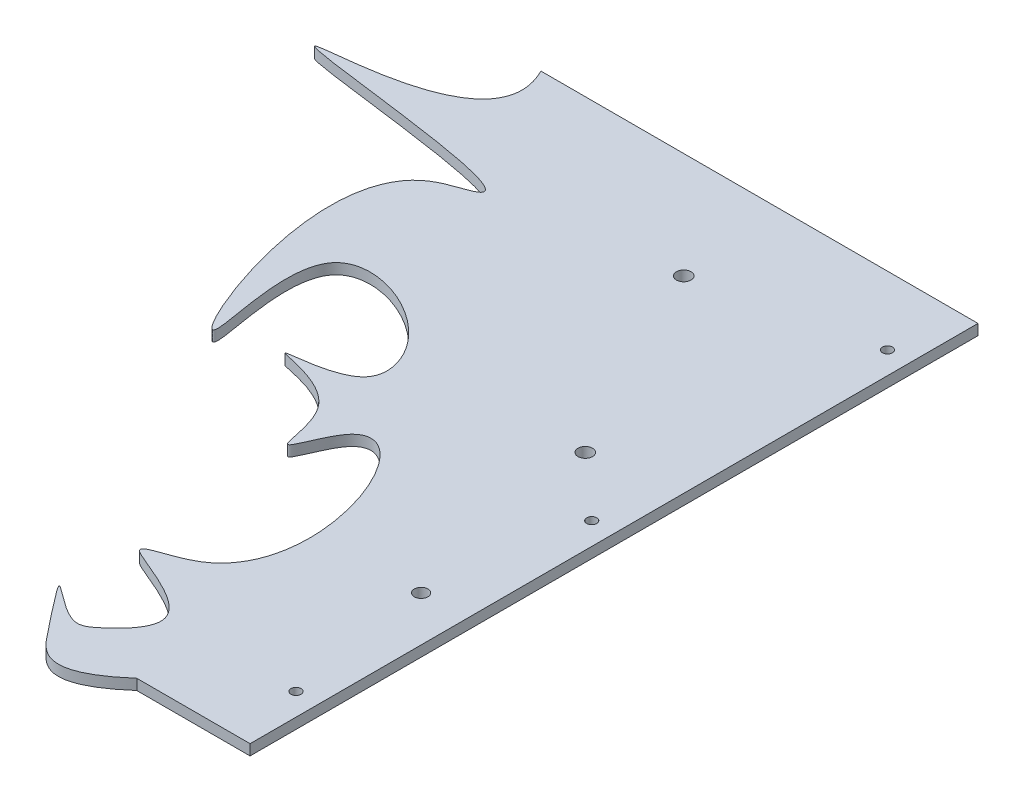
SolidWorks part; units mm, degrees
ref_plane "Front Plane" through (0, 0, 0) normal (0, 0, 1) x (1, 0, 0)
ref_plane "Top Plane" through (0, 0, 0) normal (0, 1, 0) x (1, 0, 0)
ref_plane "Right Plane" through (0, 0, 0) normal (1, 0, 0) x (0, 0, -1)
sketch "Sketch1" plane through (0, 0, 0) normal (0, 1, 0) x (1, 0, 0)
  line L0 (23.9141, 88.9) -> (-90.3859, 203.2)
  line L1 (0, 0) -> (50.8, 0)
  line L2 (0, 0) -> (0, 203.2)
  line L3 (0, 203.2) -> (50.8, 203.2)
  line L4 (50.8, 0) -> (50.8, 203.2)
  line L6 (0, 101.6) -> (0, 203.2)
  line L9 (-90.3859, 203.2) -> (0, 203.2)
  circle A0 centre (19.05, 60.325) radius 1.905
  circle A1 centre (25.4, 19.05) radius 1.397
  circle A3 centre (25.4, 101.6) radius 1.397
  circle A4 centre (25.4, 184.15) radius 1.397
  circle A5 centre (-20.9229, 173.6125) radius 2.032
  circle A6 centre (8.0019, 117.1958) radius 2.032
  point P20 (8.0019, 117.1958)
  point P21 (-20.9229, 173.6125)
  dimension "D3" = 3.81
  dimension "D9" = 2.794
  dimension "D14" = 4.064
  dimension "D15" = 4.064
  dimension "D1" = 203.2
  dimension "D2" = 50.8
  dimension "D4" = 26.8859
  dimension "D5" = 19.05
  dimension "D6" = 25.4
  dimension "D7" = 45
  dimension "D8" = 88.9
  dimension "D11" = 19.05
  dimension "D12" = 60.325
  dimension "D13" = 31.75
  dimension "D10" = 3
extrude "Boss-Extrude1" add sketch "Sketch1" along normal blind 2.9718
fillet "Fillet2" [suppressed] radius 17.78
sketch "Sketch2" plane through (0, 2.9718, 0) normal (0, 1, 0) x (1, 0, 0)
  spline S0 degree 3 poles (0, 0) (-14.4646, -12.6957) (-45.3662, 26.0149) (-25.2914, 1.7903) (-15.7444, 7.8074) (-4.3611, 20.2164) (-20.9257, 26.8985) (-34.3907, 32.6052) (7.6752, 37.8722) (-23.3746, 114.6978) (-36.7042, 69.8936) (-36.1315, 97.5495) (-70.6417, 99.5006) (-37.8553, 100.4968) (-40.7565, 124.8386) (-85.4308, 143.1876) (-60.951, 57.652) (-103.8239, 156.5637) (-47.6309, 169.6474) (-186.5705, 180.2361) (-78.0053, 178.492) (-90.3859, 203.2) knots 0 0 0 0 0.007218 0.04533 0.054764 0.083217 0.130285 0.137597 0.165213 0.280552 0.307038 0.338457 0.381582 0.421093 0.443122 0.520121 0.590944 0.735519 0.757642 0.887963 1 1 1 1
  point P2 (0, 0)
  point P4 (0, 0)
  point P6 (0, 0)
  point P8 (-90.3859, 203.2)
extrude "Boss-Extrude2" add sketch "Sketch2" against normal blind 2.9718
sketch "Sketch3" plane through (0, 2.9718, 0) normal (0, 1, 0) x (1, 0, 0)
  line L0 (-90.3859, 203.2) -> (50.8, 203.2) construction
  line L1 (50.8, 0) -> (31.6309, 0)
  line L2 (50.8, 0) -> (50.8, 203.2)
  line L3 (50.8, 203.2) -> (31.6309, 203.2)
  line L4 (31.6309, 0) -> (31.6309, 203.2)
extrude "Cut-Extrude1" cut sketch "Sketch3" against normal blind 2.9718
